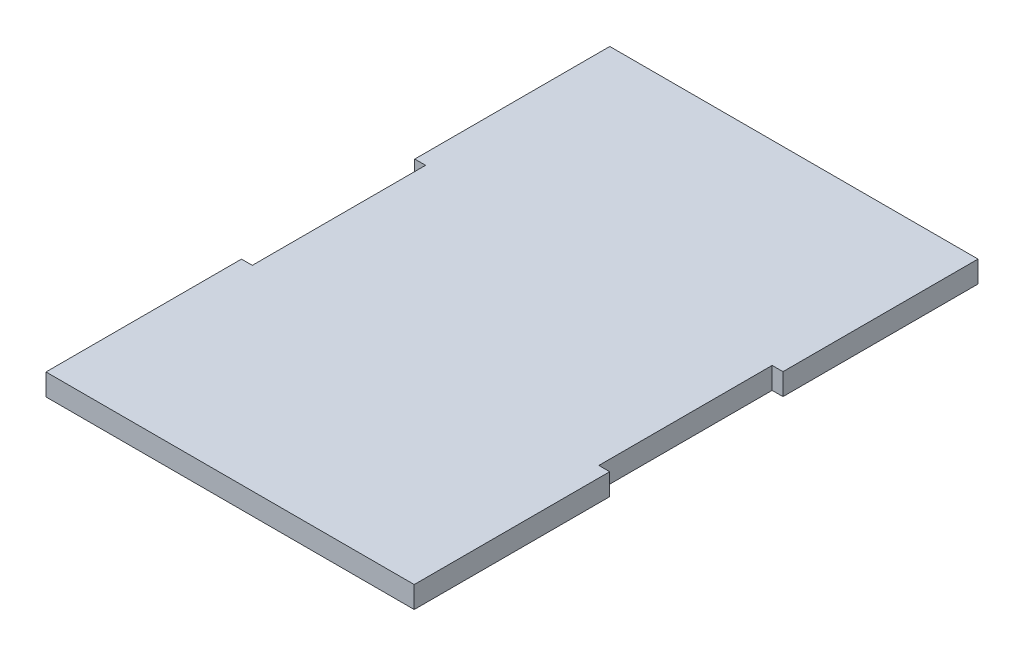
SolidWorks part; units mm, degrees
material "AISI 4130 Steel, annealed at 865C"
ref_plane "X-Y Datum" through (0, 0, 0) normal (0, 0, 1) x (1, 0, 0)
ref_plane "X-Z Datum" through (0, 0, 0) normal (0, 1, 0) x (1, 0, 0)
ref_plane "Y-Z Datum" through (0, 0, 0) normal (1, 0, 0) x (0, 0, -1)
sketch "Sketch1" plane through (0, 0, 0) normal (0, 1, 0) x (1, 0, 0)
  line L0 (-13.4937, -20.6597) -> (-13.4937, -6.3341) construction
  line L1 (-13.4937, -20.6597) -> (13.4937, -20.6597)
  line L2 (-13.4937, -20.6597) -> (-13.4937, 20.6597)
  line L3 (-13.4937, 20.6597) -> (13.4937, 20.6597)
  line L4 (13.4937, -20.6597) -> (13.4937, 20.6597)
  line L5 (-13.4937, -20.6597) -> (13.4937, 20.6597) construction
  line L6 (-13.4937, 20.6597) -> (13.4937, -20.6597) construction
  line L7 (0, -43.0151) -> (0, 43.0151) construction
  line L8 (-13.4937, -6.3341) -> (-12.7, -6.3341)
  line L9 (-13.4937, -6.3341) -> (-13.4937, 6.3659)
  line L10 (-13.4937, 6.3659) -> (-12.7, 6.3659)
  line L11 (-12.7, -6.3341) -> (-12.7, 6.3659)
  line L12 (13.4937, -6.3341) -> (12.7, -6.3341)
  line L13 (12.7, -6.3341) -> (12.7, 6.3659)
  line L14 (13.4937, 6.3659) -> (12.7, 6.3659)
  point P1 (0, 0)
  dimension "D1" = 41.3194
  dimension "D2" = 26.9875
  dimension "D3" = 14.3256
  dimension "D4" = 0.7937
  dimension "D5" = 12.7
extrude "Boss-Extrude1" add sketch "Sketch1" along normal blind 1.5875 contours L14 L4 L3 L2 L10 L11 L8 L1 L12 L13
